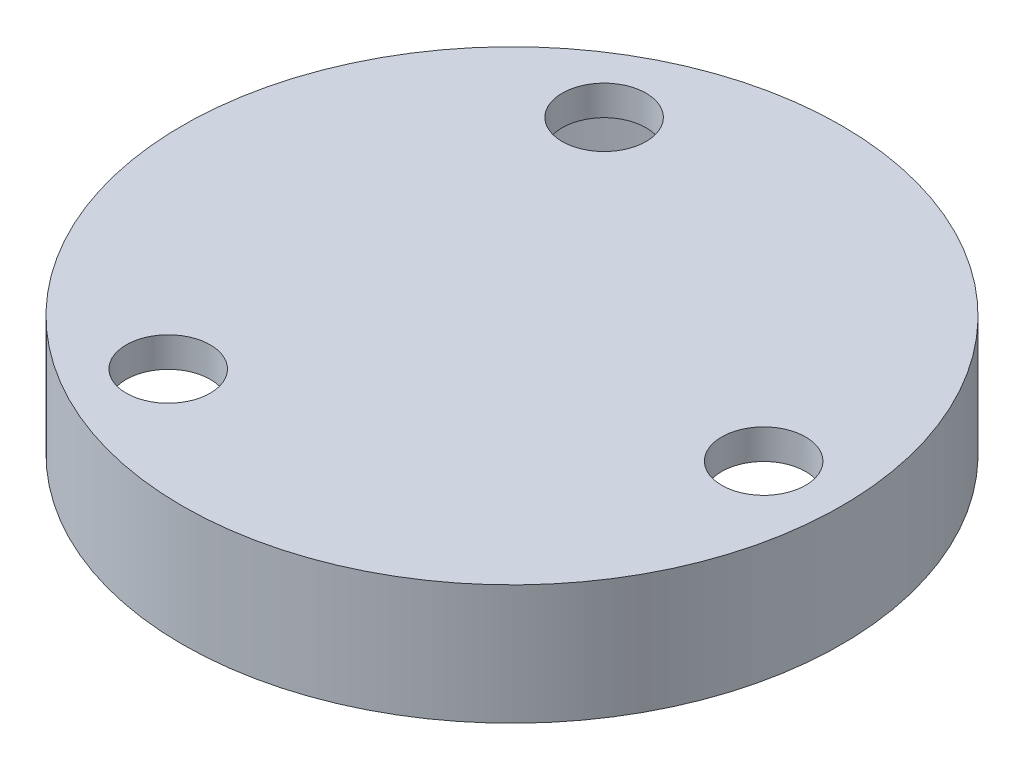
SolidWorks part; units mm, degrees
ref_plane "Front Plane" through (0, 0, 0) normal (0, 0, 1) x (1, 0, 0)
ref_plane "Top Plane" through (0, 0, 0) normal (0, 1, 0) x (1, 0, 0)
ref_plane "Right Plane" through (0, 0, 0) normal (1, 0, 0) x (0, 0, -1)
sketch "Sketch1" plane through (0, 0, 0) normal (0, 1, 0) x (1, 0, 0)
  circle A0 centre (0, 0) radius 55
  dimension "D1" = 110
extrude "Boss-Extrude1" add sketch "Sketch1" along normal blind 20
sketch "Sketch2" plane through (0, 0, 0) normal (0, -1, 0) x (1, 0, 0)
  circle A0 centre (0, 0) radius 50
  dimension "D1" = 100
extrude "Cut-Extrude1" cut sketch "Sketch2" against normal blind 15
hole_wizard "Ø1.0mm Dowel Hole1" positions "Sketch4" profile "Sketch6" hole size "Ø1.0" standard "ISO" end condition through all
sketch "Sketch4" plane through (0, 20, 0) normal (0, 1, 0) x (1, 0, 0)
  line L0 (0, 0) -> (42, 0) construction
  line L2 (0, 0) -> (-21, 36.3731) construction
  line L4 (0, 0) -> (-21, -36.3731) construction
  circle A1 centre (0, 0) radius 42 construction
  point P0 (42, 0)
  point P2 (-21, 36.3731)
  point P4 (-21, -36.3731)
  dimension "D3" = 84
  dimension "D1" = 120
  dimension "D2" = 120
sketch "Sketch6" plane through (42, 20, 0) normal (1, 0, 0) x (0, 0, 1)
  line L0 (0, 0) -> (0, 20)
  line L1 (0, 20) -> (7, 20)
  line L2 (7, 20) -> (7, 0)
  line L5 (7, 0) -> (0, 0)
  line L11 (0, -6.35) -> (0, 107.95) construction
  dimension "Thru Hole Dia." = 14
  dimension "Thru Hole Depth" = 20
